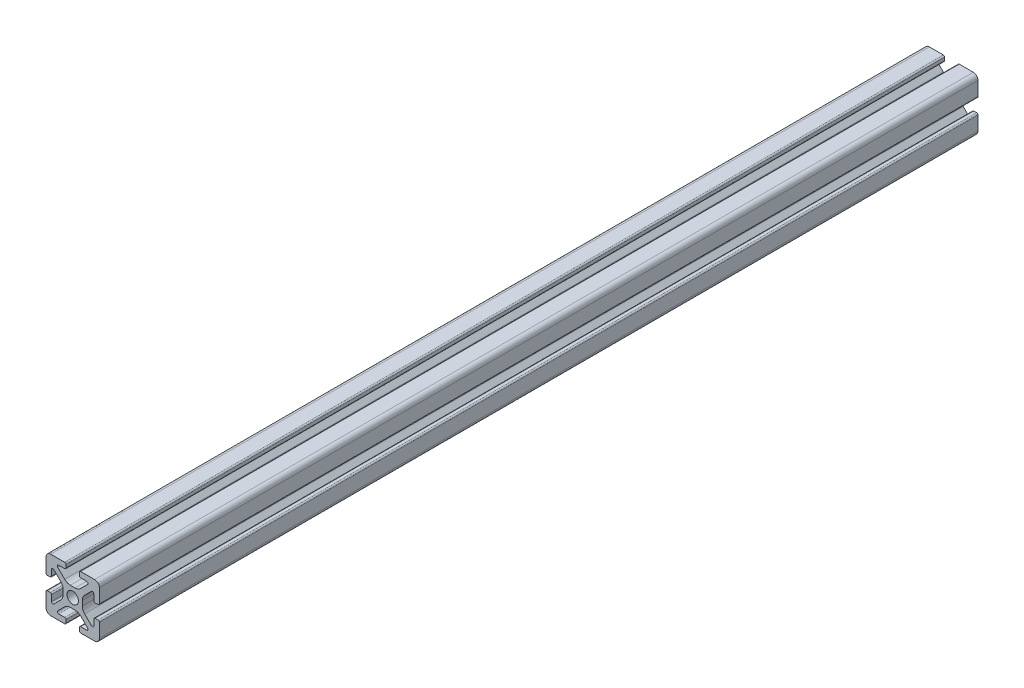
SolidWorks part; units mm, degrees
ref_plane "Front Plane" through (0, 0, 0) normal (0, 0, 1) x (1, 0, 0)
ref_plane "Top Plane" through (0, 0, 0) normal (0, 1, 0) x (1, 0, 0)
ref_plane "Right Plane" through (0, 0, 0) normal (1, 0, 0) x (0, 0, -1)
sketch "Sketch2" plane through (0, 0, 0) normal (0, 0, 1) x (1, 0, 0)
  line L0 (0, 10) -> (0, -10) construction
  line L1 (-10, 0) -> (10, 0) construction
  line L2 (2.5, -10) -> (10, -10)
  line L3 (10, -10) -> (10, -2.5)
  line L4 (2.5, -10) -> (2.5, -7.9246)
  line L5 (2.5, -7.9246) -> (6.4571, -7.9246)
  line L6 (6.4571, -7.9246) -> (2.1325, -3.6)
  line L7 (0, 0) -> (10, -10) construction
  line L8 (10, -2.5) -> (7.9246, -2.5)
  line L9 (7.9246, -2.5) -> (7.9246, -6.4571)
  line L10 (7.9246, -6.4571) -> (3.6, -2.1325)
  line L11 (5.7623, -4.2948) -> (4.2948, -5.7623) construction
  circle A0 centre (0, 0) radius 2.15
  arc A1 (5.25, -7.9246) -> (5.6036, -7.0711) centre (5.25, -7.4246) ccw construction
  point P8 (0, -3.6)
  point P16 (5.0286, -5.0286)
  dimension "Center Hole Diameter" = 4.3
  dimension "D3" = 0.5
  dimension "Rail Height" = 20
  dimension "Rail Width" = 20
  dimension "T-Slot Width" = 5
  dimension "Slot Depth" = 6.4
  dimension "Slot Inner Width" = 11.5
sketch "Sketch3" plane through (0, 0, 0) normal (1, 0, 0) x (0, 0, -1)
  line L0 (-304.8, -10) -> (304.8, -10) construction
  line L1 (-279.4, 0) -> (279.4, 0) construction
  line L2 (0, 10) -> (0, -10) construction
  line L3 (0, 10) -> (0, -10) construction
  point P6 (-279.4, 0)
  point P8 (279.4, 0)
  dimension "Length" = 609.6
  dimension "D1" = 25.4
sketch "Sketch4" plane through (0, 0, 0) normal (0, 0, 1) x (1, 0, 0)
  line L0 (3, -10) -> (8.25, -10)
  line L1 (2.5, -10) -> (10, -10) construction
  line L2 (2.5, -10) -> (2.5, -7.9246) construction
  line L3 (2.5, -7.9246) -> (6.4571, -7.9246) construction
  line L4 (2.5, -8.4246) -> (2.5, -9.5)
  line L5 (3, -7.9246) -> (5.25, -7.9246)
  line L6 (0, -3.6) -> (0.8898, -3.6)
  line L7 (6.4571, -7.9246) -> (2.1325, -3.6) construction
  line L8 (3.0112, -4.4787) -> (5.6036, -7.0711)
  line L9 (10, -10) -> (10, -2.5) construction
  line L10 (7.9246, -6.4571) -> (3.6, -2.1325) construction
  line L11 (7.9246, -2.5) -> (7.9246, -6.4571) construction
  line L12 (7.9246, -5.25) -> (7.9246, -3)
  line L13 (10, -2.5) -> (7.9246, -2.5) construction
  line L14 (8.4246, -2.5) -> (9.5, -2.5)
  line L15 (10, -3) -> (10, -8.25)
  line L16 (7.0711, -5.6036) -> (4.4787, -3.0112)
  line L17 (3.6, 0) -> (3.6, -0.8898)
  line L18 (-10, 0) -> (10, 0) construction
  line L19 (0, -3.6) -> (0, -2.15)
  line L20 (0, 10) -> (0, -10) construction
  line L21 (3.6, 0) -> (2.15, 0)
  arc A0 (2.5, -9.5) -> (3, -10) centre (3, -9.5) ccw
  arc A1 (5.25, -7.9246) -> (5.6036, -7.0711) centre (5.25, -7.4246) ccw construction
  arc A2 (2.5, -8.4246) -> (3, -7.9246) centre (3, -8.4246) cw
  arc A3 (5.25, -7.9246) -> (5.6036, -7.0711) centre (5.25, -7.4246) ccw
  arc A4 (0.8898, -3.6) -> (3.0112, -4.4787) centre (0.8898, -6.6) cw
  arc A5 (8.25, -10) -> (10, -8.25) centre (8.25, -8.25) ccw
  arc A6 (7.0711, -5.6036) -> (7.9246, -5.25) centre (7.4246, -5.25) ccw
  arc A7 (7.9246, -3) -> (8.4246, -2.5) centre (8.4246, -3) cw
  arc A8 (9.5, -2.5) -> (10, -3) centre (9.5, -3) cw
  arc A9 (4.4787, -3.0112) -> (3.6, -0.8898) centre (6.6, -0.8898) cw
  circle A10 centre (0, 0) radius 2.15 construction
  arc A11 (0, -2.15) -> (2.15, 0) centre (0, 0) ccw
  dimension "D1" = 1.75
  dimension "D2" = 3
extrude "Boss-Extrude1" add sketch "Sketch4" along normal mid plane 609.6
mirror "Mirror1" about plane through (0, 0, 0) normal (1, 0, 0) of bodies 134
mirror "Mirror2" about plane through (0, 0, 0) normal (0, 1, 0) of bodies 135
sketch "Sketch5" plane through (0, 0, -304.8) normal (0, 0, -1) x (-1, 0, 0)
  line L1 (-13.8311, 12.3183) -> (13.1641, 12.3183)
  line L2 (-13.8311, 12.3183) -> (-13.8311, -12.3688)
  line L3 (-13.8311, -12.3688) -> (13.1641, -12.3688)
  line L4 (13.1641, 12.3183) -> (13.1641, -12.3688)
extrude "Cut-Extrude1" cut sketch "Sketch5" against normal blind 280.025
equation "\"D3@Sketch2\"=\"T-Slot Width@Sketch2\"*0.1"
equation "\"D1@Sketch4\"=\"D3@Sketch2\"*3.5"
equation "\"D2@Sketch4\"=\"D3@Sketch2\"*6"
equation "\"D1@Boss-Extrude1\"=\"Length@Sketch3\""
